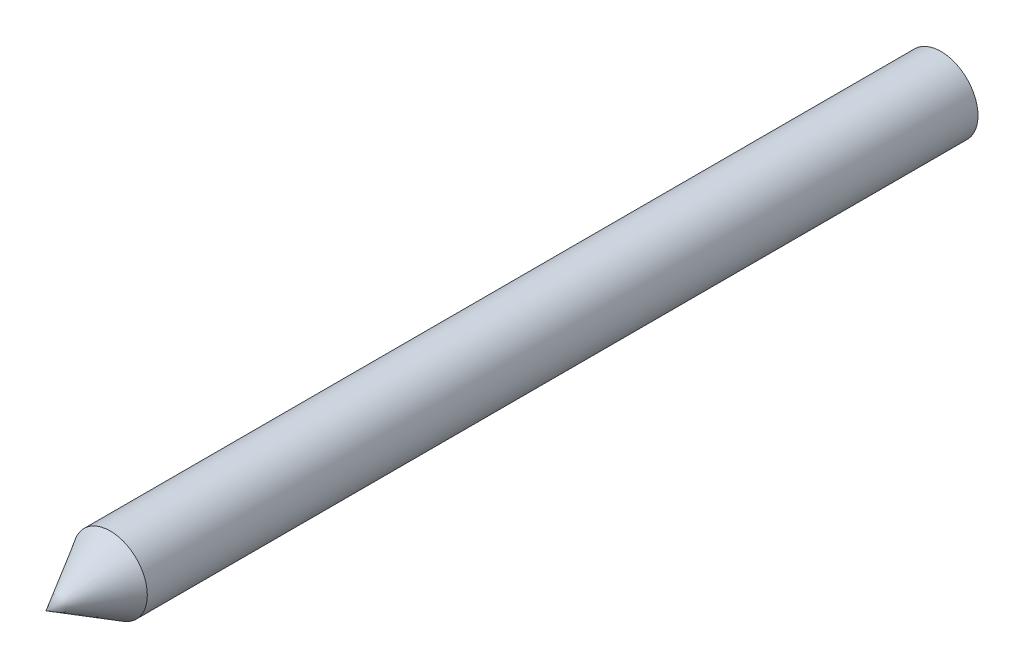
SolidWorks part; units mm, degrees
ref_plane "Front Plane" through (0, 0, 0) normal (0, 0, 1) x (1, 0, 0)
ref_plane "Top Plane" through (0, 0, 0) normal (0, 1, 0) x (1, 0, 0)
ref_plane "Right Plane" through (0, 0, 0) normal (1, 0, 0) x (0, 0, -1)
sketch "Sketch1" plane through (0, 0, 0) normal (0, 0, 1) x (1, 0, 0)
  circle A0 centre (0, 0) radius 7.9375
  dimension "D1" = 15.875
extrude "Boss-Extrude1" add sketch "Sketch1" along normal mid plane 177.8
sketch "Sketch3" plane through (0, 0, 0) normal (1, 0, 0) x (0, 0, -1)
  line L0 (0, 0) -> (-259.5858, 0) construction
  line L1 (-88.9, 7.9375) -> (-102.6482, 0)
  line L3 (-88.9, 0) -> (-88.9, 7.9375)
  line L4 (-102.6482, 0) -> (-88.9, 0) construction
  line L5 (-102.6482, 0) -> (-88.9, 0)
  dimension "D1" = 30
revolve "Revolve2" add sketch "Sketch3" angle 360 about L0
